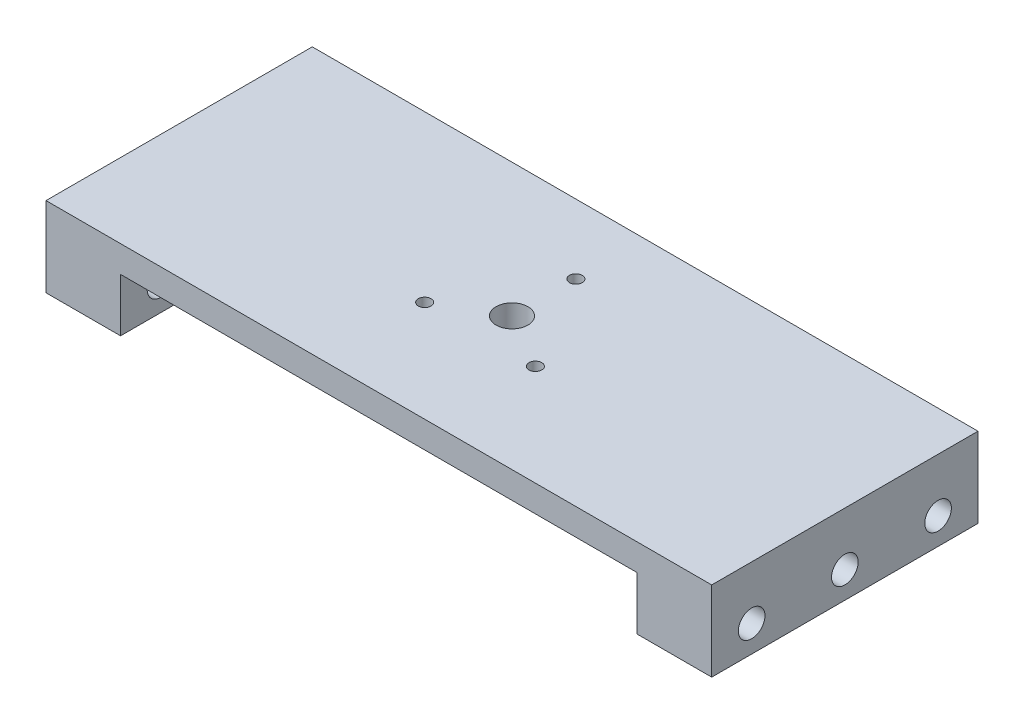
SolidWorks part; units mm, degrees
material "1060 合金"
ref_plane "前视基准面" through (0, 0, 0) normal (0, 0, 1) x (1, 0, 0)
ref_plane "上视基准面" through (0, 0, 0) normal (0, 1, 0) x (1, 0, 0)
ref_plane "右视基准面" through (0, 0, 0) normal (1, 0, 0) x (0, 0, -1)
sketch "草图1" plane through (0, 0, 0) normal (0, 1, 0) x (1, 0, 0)
  line L0 (0, -50) -> (125, -50)
  line L1 (0, -50) -> (-125, -50)
  line L2 (-125, -50) -> (-125, 50)
  line L3 (-125, 50) -> (125, 50)
  line L4 (125, 50) -> (125, -50)
  dimension "D1" = 100
  dimension "D2" = 125
  dimension "D3" = 125
  dimension "D4" = 50
extrude "凸台-拉伸1" add sketch "草图1" along normal blind 10
sketch "草图4" plane through (0, 0, 0) normal (0, -1, 0) x (1, 0, 0)
  line L0 (-125, 50) -> (-125, -50)
  line L1 (-125, 50) -> (-97, 50)
  line L2 (-97, 50) -> (-97, -50)
  line L3 (125, -50) -> (-125, -50) construction
  line L4 (-97, -50) -> (-125, -50)
  dimension "D1" = 0
  dimension "D2" = 28
  dimension "D3" = 28
extrude "凸台-拉伸2" add sketch "草图4" along normal blind 20
mirror "镜向1" about plane through (0, 0, 0) normal (1, 0, 0) of "凸台-拉伸2"
sketch "草图5" plane through (125, 0, 0) normal (1, 0, 0) x (0, 0, -1)
  line L0 (-50, -20) -> (50, -20) construction
  circle A0 centre (0, -10) radius 5
  circle A1 centre (-35, -10) radius 5
  circle A2 centre (35, -10) radius 5
  dimension "D1" = 10
  dimension "D4" = 35
  dimension "D2" = 10
  dimension "D3" = 10
  dimension "D5" = 35
  dimension "D6" = 0
extrude "切除-拉伸2" cut sketch "草图5" against normal blind 30
mirror "镜向2" about plane through (0, 0, 0) normal (1, 0, 0) of "切除-拉伸2"
sketch "草图9" plane through (0, 10, 0) normal (0, 1, 0) x (1, 0, 0)
  circle A0 centre (0, 24) radius 2.4
  circle A1 centre (20.7846, -12) radius 2.4
  circle A2 centre (-20.7846, -12) radius 2.4
  point P9 (0, 0)
  point P27 (0, 0)
  dimension "D1" = 3
extrude "切除-拉伸4" cut sketch "草图9" against normal blind 10
sketch "草图10" plane through (0, 10, 0) normal (0, 1, 0) x (1, 0, 0)
  circle A0 centre (0, 0) radius 6
extrude "切除-拉伸5" cut sketch "草图10" against normal blind 10
